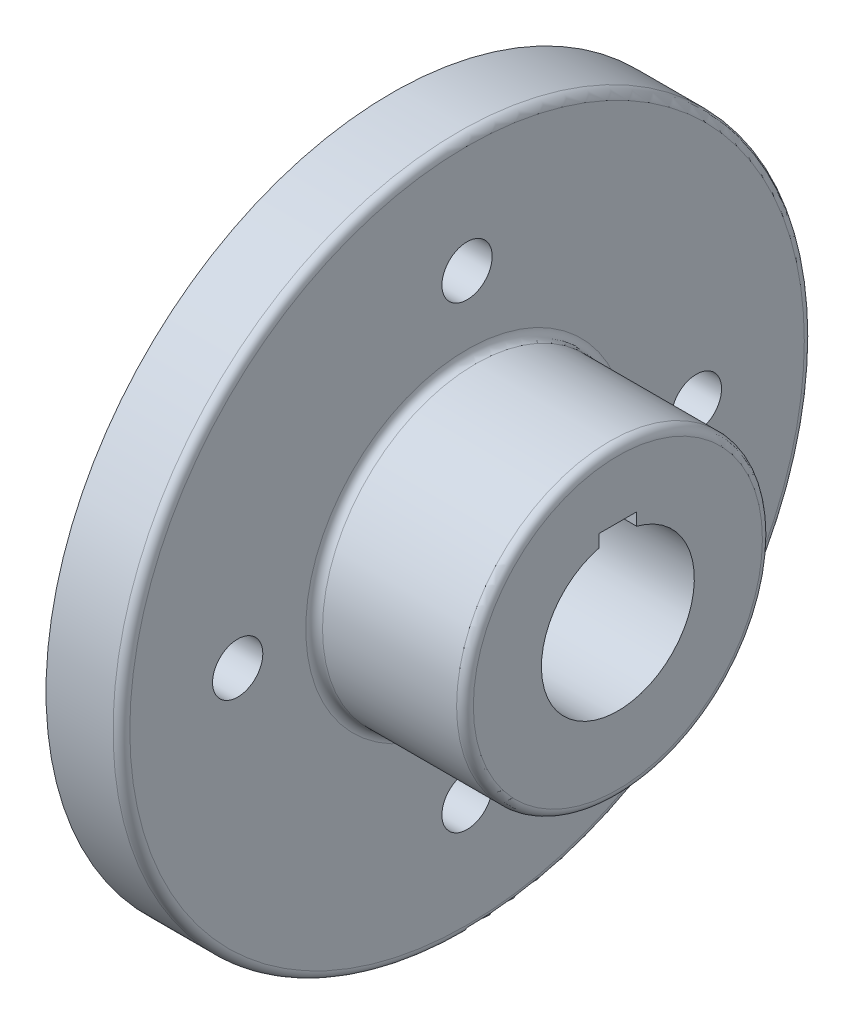
SolidWorks part; units mm, degrees
ref_plane "Front Plane" through (0, 0, 0) normal (0, 0, 1) x (1, 0, 0)
ref_plane "Top Plane" through (0, 0, 0) normal (0, 1, 0) x (1, 0, 0)
ref_plane "Right Plane" through (0, 0, 0) normal (1, 0, 0) x (0, 0, -1)
sketch "Sketch1" plane through (0, 0, 0) normal (1, 0, 0) x (0, 0, -1)
  circle A0 centre (0, 0) radius 82.5
  dimension "D1" = 165
extrude "Boss-Extrude1" add sketch "Sketch1" along normal blind 18
sketch "Sketch2" plane through (18, 0, 0) normal (1, 0, 0) x (0, 0, -1)
  circle A0 centre (0, 0) radius 36.5
  dimension "D1" = 73
extrude "Boss-Extrude2" add sketch "Sketch2" along normal blind 36
sketch "Sketch3" plane through (0, 0, 0) normal (-1, 0, 0) x (0, 0, 1)
  circle A0 centre (0, 0) radius 18.25
  dimension "D1" = 36.5
extrude "Cut-Extrude1" cut sketch "Sketch3" against normal through all
sketch "Sketch4" plane through (0, 0, 0) normal (-1, 0, 0) x (0, 0, 1)
  line L0 (0, 0) -> (0, -108.0609) construction
  circle A0 centre (0, -54.75) radius 6
  circle A1 centre (-54.75, 0) radius 6
  circle A2 centre (0, 54.75) radius 6
  circle A3 centre (54.75, 0) radius 6
  point P14 (0, 0)
  dimension "D1" = 12
  dimension "D2" = 54.75
  dimension "D3" = 4
extrude "Cut-Extrude2" cut sketch "Sketch4" against normal through all
fillet "Fillet1" radius 2 3 edges at (18, 0, -82.5) (18, 0, -36.5) (54, 0, -36.5)
sketch "Sketch5" plane through (0, 0, 0) normal (-1, 0, 0) x (0, 0, 1)
  line L1 (-4.5, 20.6865) -> (4.5, 20.6865)
  line L2 (-4.5, 20.6865) -> (-4.5, 17.6865)
  line L3 (-4.5, 17.6865) -> (4.5, 17.6865)
  line L4 (4.5, 20.6865) -> (4.5, 17.6865)
  circle A0 centre (0, 0) radius 18.25 construction
  point P6 (0, 0)
  point P7 (0, 0)
  point P8 (0, 0)
  point P9 (0, 0)
  point P10 (0, 0)
  dimension "D1" = 3
  dimension "D2" = 9
extrude "Cut-Extrude3" cut sketch "Sketch5" against normal through all
